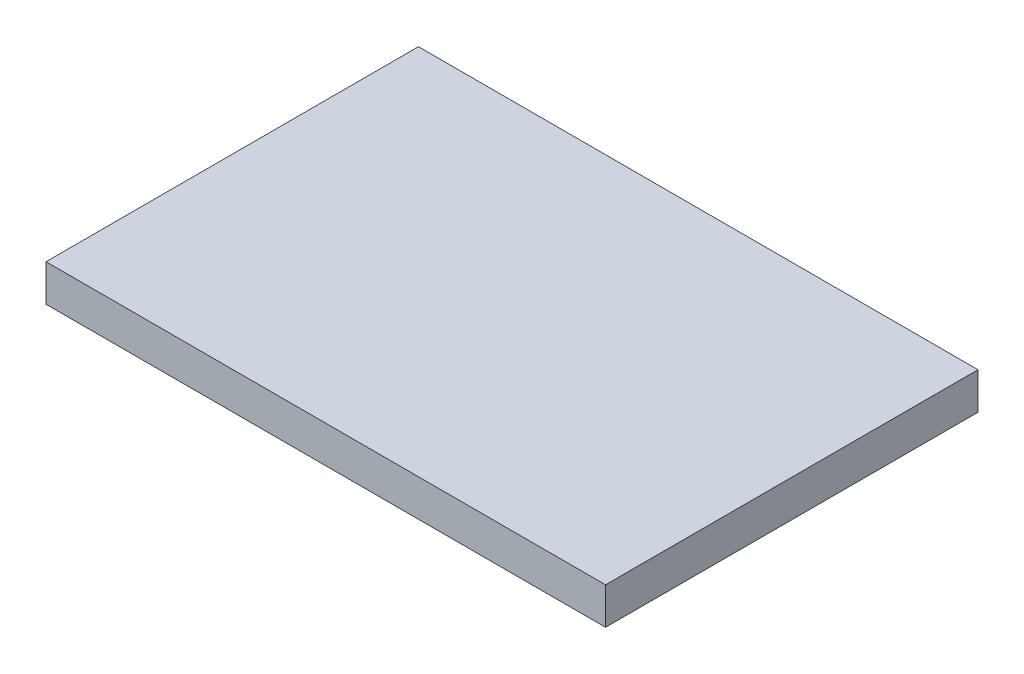
SolidWorks part; units mm, degrees
ref_plane "Front Plane" through (0, 0, 0) normal (0, 0, 1) x (1, 0, 0)
ref_plane "Top Plane" through (0, 0, 0) normal (0, 1, 0) x (1, 0, 0)
ref_plane "Right Plane" through (0, 0, 0) normal (1, 0, 0) x (0, 0, -1)
sketch "Sketch1" plane through (0, 0, 0) normal (0, 1, 0) x (1, 0, 0)
  line L1 (-23.925, 15.925) -> (23.925, 15.925)
  line L2 (-23.925, 15.925) -> (-23.925, -15.925)
  line L3 (-23.925, -15.925) -> (23.925, -15.925)
  line L4 (23.925, 15.925) -> (23.925, -15.925)
  line L5 (-23.925, 15.925) -> (23.925, -15.925) construction
  line L6 (-23.925, -15.925) -> (23.925, 15.925) construction
  point P0 (0, 0)
  dimension "D1" = 31.85
  dimension "D2" = 47.85
extrude "Boss-Extrude1" add sketch "Sketch1" against normal blind 3.15
shell "Shell1" thickness 1.5
